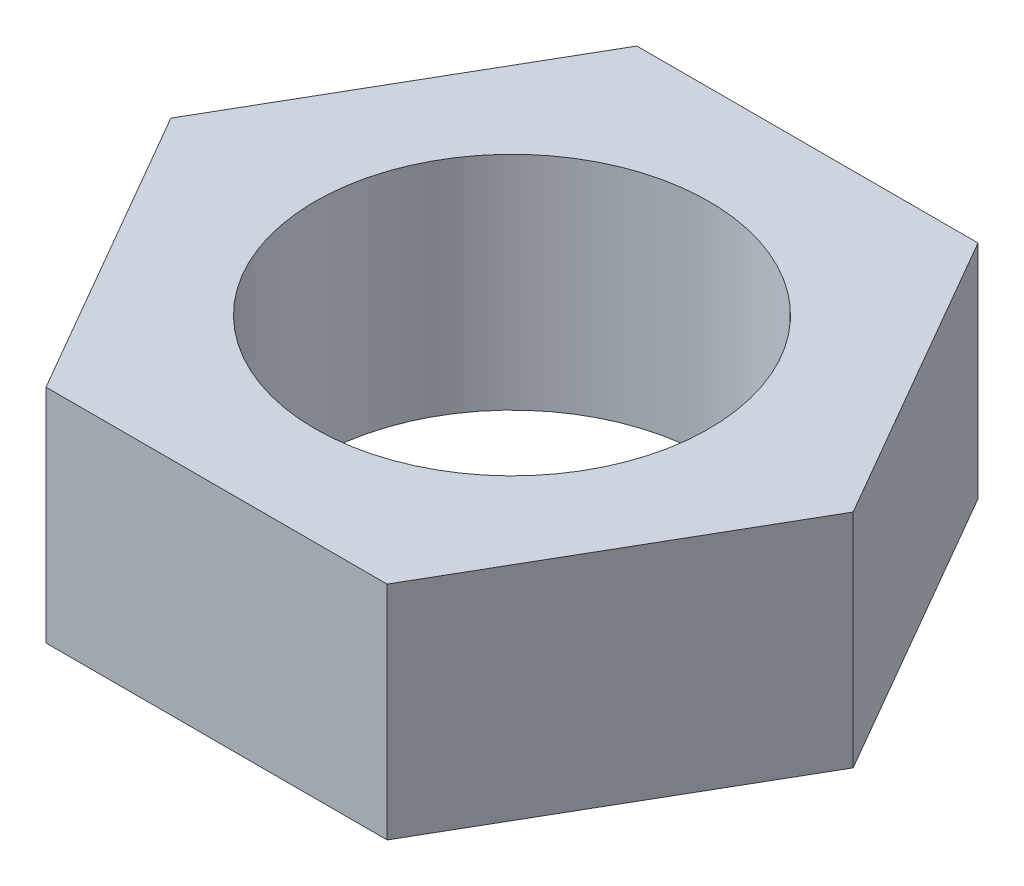
SolidWorks part; units mm, degrees
ref_plane "Front Plane" through (0, 0, 0) normal (0, 0, 1) x (1, 0, 0)
ref_plane "Top Plane" through (0, 0, 0) normal (0, 1, 0) x (1, 0, 0)
ref_plane "Right Plane" through (0, 0, 0) normal (1, 0, 0) x (0, 0, -1)
sketch "Sketch1" plane through (0, 0, 0) normal (0, 1, 0) x (1, 0, 0)
  line L0 (0, 0) -> (16.4978, 0) construction
  line L2 (8.2489, 14.2875) -> (-8.2489, 14.2875)
  line L3 (-8.2489, 14.2875) -> (-16.4978, 0)
  line L4 (-16.4978, 0) -> (-8.2489, -14.2875)
  line L5 (-8.2489, -14.2875) -> (8.2489, -14.2875)
  line L6 (8.2489, -14.2875) -> (16.4978, 0)
  line L7 (16.4978, 0) -> (8.2489, 14.2875)
  circle A0 centre (0, 0) radius 14.2875 construction
  circle A1 centre (0, 0) radius 9.525
  dimension "D2" = 19.05
  dimension "D1" = 28.575
extrude "Extrude1" add sketch "Sketch1" along normal blind 10.7156
